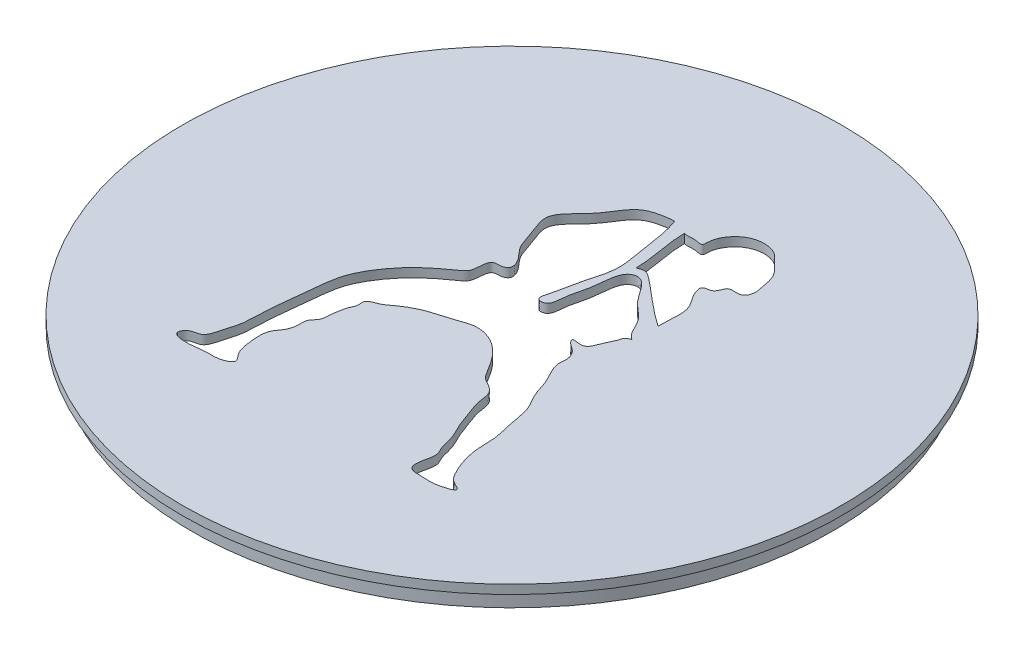
SolidWorks part; units mm, degrees
ref_plane "前视基准面" through (0, 0, 0) normal (0, 0, 1) x (1, 0, 0)
ref_plane "上视基准面" through (0, 0, 0) normal (0, 1, 0) x (1, 0, 0)
ref_plane "右视基准面" through (0, 0, 0) normal (1, 0, 0) x (0, 0, -1)
other "Configuration Table"
sketch "草图1" plane through (0, 0, 0) normal (0, 1, 0) x (1, 0, 0)
  line L0 (72.5003, 135.938) -> (362.5014, 135.938) construction
  circle A0 centre (35, 20) radius 36
  spline S0 degree 3 poles (35, 38.2587) (34.6334, 38.2753) (33.6488, 38.1296) (31.3041, 37.5388) (30.1168, 34.3357) (26.7641, 32.007) (28.1551, 29.1291) (28.6711, 26.926) (30.0294, 25.8494) (30.4315, 24.6149) (29.6975, 24.0407) (28.5879, 24.3063) (28.4125, 22.9719) (28.3998, 21.8818) (26.5228, 20.603) (24.5961, 19.0623) (22.8097, 16.6958) (21.5049, 14.2562) (21.2084, 10.6062) (20.7391, 7.2593) (20.7348, 4.8681) (20.5807, 3.5506) (20.1335, 2.3712) (19.7677, 0.4715) (18.3182, 0.588) (17.5197, -0.7471) (19.68, -1.0698) (21.2283, -0.6178) (22.8242, -0.8546) (24.2731, -0.0435) (23.1882, 0.9683) (22.9395, 2.1971) (22.7703, 3.599) (22.8625, 4.9263) (23.768, 5.8744) (24.0071, 6.9767) (23.8804, 8.0801) (24.805, 8.7726) (24.7081, 9.9649) (24.9283, 10.8222) (25.0492, 11.6097) (25.5, 12.1779) (25.1583, 13.2739) (26.5464, 13.5769) (27.6975, 14.5562) (29.6107, 15.6665) (31.8769, 16.1612) (33.7798, 16.9574) (35.5586, 16.7536) (37.2431, 15.7676) (38.3849, 14.3125) (39.0924, 13.0911) (39.6818, 12.219) (40.5359, 11.8842) (41.4881, 11.0869) (41.4522, 9.6174) (42.1486, 8.1152) (42.6393, 6.3745) (43.6145, 4.825) (43.7863, 3.3427) (44.5288, 2.1269) (44.0487, 0.9543) (43.9938, -0.7959) (45.8754, -0.6971) (47.0221, -0.898) (49.5234, -0.092) (47.8088, 0.4695) (47.1412, 1.4615) (46.4736, 2.9504) (45.9845, 4.8862) (46.1, 7.0999) (45.3813, 9.5155) (45.1607, 11.7784) (43.8777, 13.5824) (43.4997, 15.5132) (42.5303, 16.8477) (42.2526, 18.0367) (42.496, 18.9403) (41.8851, 20.1104) (41.0352, 20.4226) (40.5805, 21.2425) (42.1781, 20.664) (42.6572, 21.9009) (43.0113, 22.8056) (43.4042, 23.4716) (43.4739, 24.1735) (43.9373, 24.2795) (44.0946, 24.3748) knots 0.011137 0.011137 0.011137 0.011137 0.017895 0.02884 0.053566 0.076394 0.090782 0.105825 0.117199 0.122579 0.125774 0.132434 0.138902 0.145562 0.152221 0.177469 0.19236 0.206082 0.227671 0.258486 0.268313 0.271611 0.282626 0.293056 0.300381 0.305513 0.314184 0.327372 0.338889 0.344534 0.349971 0.359788 0.368496 0.37585 0.38314 0.391481 0.395963 0.402399 0.409753 0.41628 0.418858 0.424257 0.42873 0.436258 0.443935 0.458083 0.475465 0.48674 0.495169 0.507307 0.52159 0.528495 0.533473 0.540378 0.544929 0.555303 0.564764 0.575464 0.588352 0.597646 0.602528 0.613211 0.62025 0.628803 0.639431 0.649603 0.655454 0.662582 0.672716 0.684786 0.699069 0.712777 0.730949 0.739584 0.752674 0.766304 0.769155 0.774754 0.782934 0.790234 0.791484 0.797641 0.805749 0.812136 0.816139 0.820033 0.823536 0.823536 0.823536 0.823536
  spline S1 degree 3 poles (35, 38.2587) (35.6466, 36.4948) (35.8543, 33.9205) (36.6185, 30.111) (35.504, 27.1203) (35.2499, 24.9915) (34.6219, 22.9169) (36.1408, 22.9697) (36.1037, 25.0782) (36.8129, 26.9102) (36.8461, 28.9964) (37.2866, 30.5026) (39.0892, 31.1743) (40.3546, 28.1901) (42.8794, 26.8281) (43.3402, 24.8219) (44.0946, 24.3748) knots 0 0 0 0 0.166956 0.232571 0.347071 0.429099 0.465182 0.483664 0.532843 0.611757 0.673238 0.722617 0.734592 0.836706 0.924346 1 1 1 1
  spline S2 degree 3 poles (36.7199, 37.6531) (36.7246, 35.4362) (37.3434, 33.9976) (37.3551, 31.5045) (37.8559, 31.7859) (38.4397, 31.7649) (40.7318, 29.9945) (42.336, 28.4282) (44.2684, 27.1376) knots 0 0 0 0 0.408865 0.417465 0.441783 0.484004 0.55011 1 1 1 1
  spline S3 degree 3 poles (44.2684, 27.1376) (44.2534, 27.6534) (44.3416, 28.738) (44.4371, 30.9929) (42.9769, 32.1664) (42.9123, 33.5384) (44.257, 33.3685) (44.2789, 35.1618) (45.9428, 34.4996) (46.5367, 35.681) (46.2733, 36.963) (46.0009, 38.6354) (44.692, 39.7356) (43.7916, 40.7945) (42.47, 41.2245) (41.0652, 41.0524) (39.8526, 40.2616) (39.1045, 39.186) (38.8704, 38.3109) (38.9016, 37.3479) (37.845, 37.7194) (37.1945, 37.5254) (36.8015, 37.6258) (36.7199, 37.6531) knots 0.840262 0.840262 0.840262 0.840262 0.849614 0.86199 0.878687 0.879473 0.885979 0.893394 0.902121 0.907245 0.913938 0.926248 0.936823 0.944332 0.951417 0.961313 0.969271 0.977449 0.984313 0.986958 0.992068 0.998356 1 1 1 1
  dimension "D1" = 72
  dimension "D2" = 35
  dimension "D3" = 20
extrude "凸台-拉伸1" add sketch "草图1" along normal blind 1
sketch "草图2" plane through (0, 0, 0) normal (0, -1, 0) x (-1, 0, 0)
  circle A0 centre (-35, 20) radius 36
  circle A1 centre (-35, 20) radius 35
  dimension "D1" = 1
extrude "凸台-拉伸2" add sketch "草图2" along normal blind 2
sketch "草图3" plane through (0, 1, 0) normal (0, 1, 0) x (1, 0, 0)
  circle A0 centre (35, 20) radius 36
  circle A1 centre (35, 20) radius 37
  dimension "D1" = 1
extrude "凸台-拉伸3" add sketch "草图3" against normal blind 1
